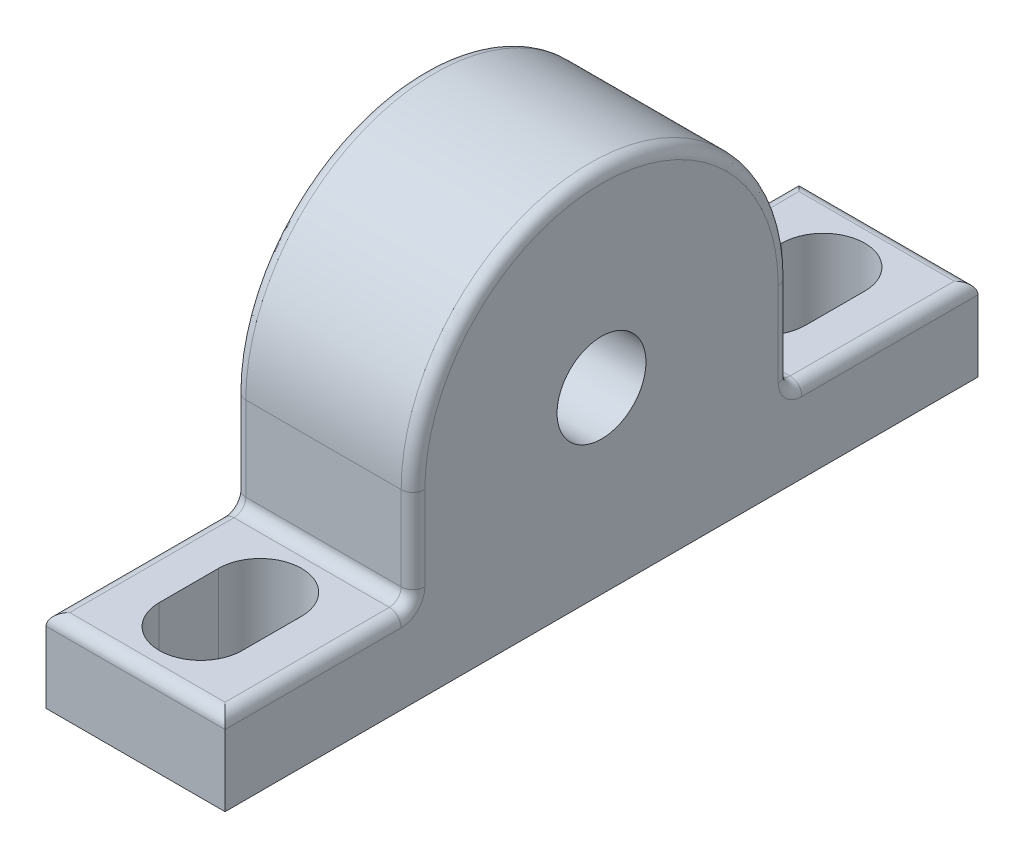
SolidWorks part; units mm, degrees
ref_plane "Płaszczyzna przednia" through (0, 0, 0) normal (0, 0, 1) x (1, 0, 0)
ref_plane "Płaszczyzna górna" through (0, 0, 0) normal (0, 1, 0) x (1, 0, 0)
ref_plane "Płaszczyzna prawa" through (0, 0, 0) normal (1, 0, 0) x (0, 0, -1)
sketch "Szkic1" plane through (0, 0, 0) normal (1, 0, 0) x (0, 0, -1)
  line L7 (31.8, 14) -> (63.5, 14)
  line L8 (-63.5, 0) -> (63.5, 0)
  line L9 (-63.5, 0) -> (-63.5, 14)
  line L10 (-63.5, 14) -> (-31.8, 14)
  line L11 (63.5, 0) -> (63.5, 14)
  line L12 (-31.8, 30.2) -> (-31.8, 14)
  line L13 (31.8, 30.2) -> (31.8, 14)
  arc A1 (31.8, 30.2) -> (-31.8, 30.2) centre (0, 30.2) ccw
  dimension "D3" = 30.2
  dimension "D4" = 63.6
  dimension "D1" = 127
  dimension "D2" = 14
extrude "Dodanie-wyciągnięcie1" add sketch "Szkic1" along normal blind 30.2
sketch "Szkic2" plane through (30.2, 0, 0) normal (1, 0, 0) x (0, 0, -1)
  circle A0 centre (0, 30.2) radius 7.5
  arc A3 (31.8, 30.2) -> (-31.8, 30.2) centre (0, 30.2) ccw construction
  dimension "D1" = 15
extrude "Wytnij-wyciągnięcie1" cut sketch "Szkic2" against normal through all
fillet "Zaokrąglenie1" radius 2 14 edges at (30.2, 14, -47.65) (0, 14, -47.65) (30.2, 22.1, -31.8) (0, 22.1, -31.8) (30.2, 62, 0) (0, 62, 0) (30.2, 22.1, 31.8) (0, 22.1, 31.8) (15.1, 14, 31.8) (30.2, 14, 47.65) (15.1, 14, 63.5) (0, 14, 47.65) (15.1, 14, -63.5) (15.1, 14, -31.8)
sketch "Szkic3" plane through (0, 14, 0) normal (0, 1, 0) x (1, 0, 0)
  line L0 (15.1, -52.5) -> (15.1, -42.5) construction
  line L1 (8.1, -52.5) -> (8.1, -42.5)
  line L2 (22.1, -52.5) -> (22.1, -42.5)
  line L3 (15.1, 42.5) -> (15.1, 52.5) construction
  line L4 (8.1, 42.5) -> (8.1, 52.5)
  line L5 (22.1, 42.5) -> (22.1, 52.5)
  line L7 (0, 0) -> (-28.9568, 0) construction
  line L8 (2, -33.8) -> (2, -61.5) construction
  line L9 (28.2, -61.5) -> (28.2, -33.8) construction
  arc A0 (8.1, -52.5) -> (22.1, -52.5) centre (15.1, -52.5) ccw
  arc A1 (22.1, -42.5) -> (8.1, -42.5) centre (15.1, -42.5) ccw
  arc A2 (8.1, 42.5) -> (22.1, 42.5) centre (15.1, 42.5) ccw
  arc A3 (22.1, 52.5) -> (8.1, 52.5) centre (15.1, 52.5) ccw
  point P2 (15.1, -47.5)
  point P7 (15.1, 47.5)
  dimension "D1" = 7
  dimension "D2" = 10
  dimension "D3" = 95
extrude "Wytnij-wyciągnięcie2" cut sketch "Szkic3" against normal up to next
